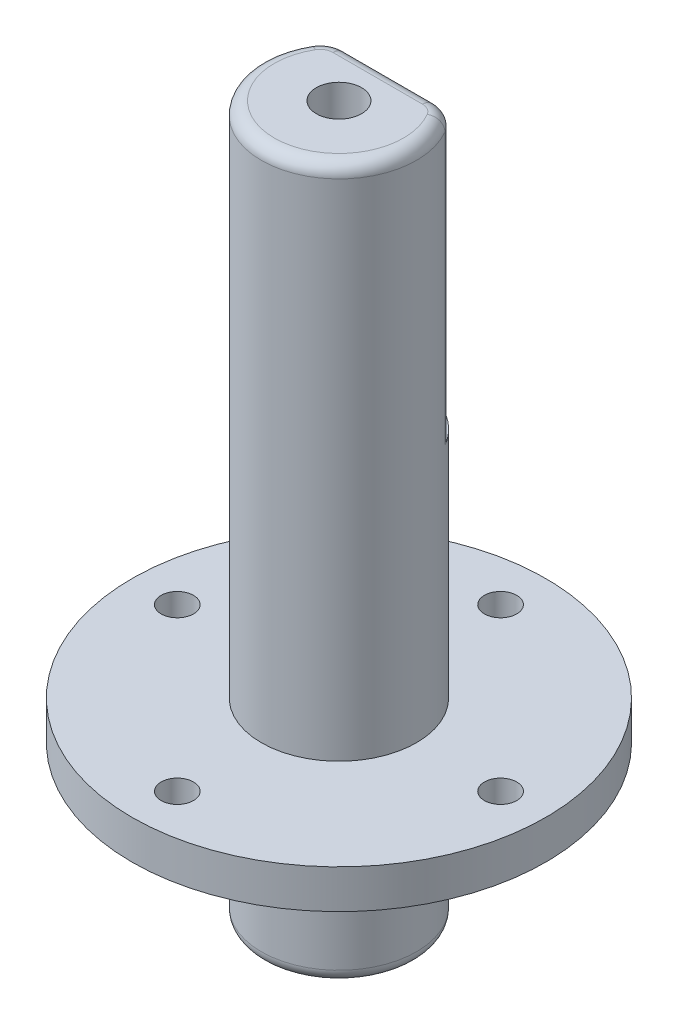
SolidWorks part; units mm, degrees
ref_plane "Front Plane" through (0, 0, 0) normal (0, 0, 1) x (1, 0, 0)
ref_plane "Top Plane" through (0, 0, 0) normal (0, 1, 0) x (1, 0, 0)
ref_plane "Right Plane" through (0, 0, 0) normal (1, 0, 0) x (0, 0, -1)
sketch "Sketch1" plane through (0, 0, 0) normal (0, 1, 0) x (1, 0, 0)
  circle A0 centre (0, 0) radius 6
  dimension "D1" = 12
extrude "Boss-Extrude1" add sketch "Sketch1" along normal blind 10
sketch "Sketch2" plane through (0, 10, 0) normal (0, 1, 0) x (1, 0, 0)
  circle A0 centre (0, 0) radius 10
  dimension "D1" = 20
extrude "Boss-Extrude2" add sketch "Sketch2" along normal blind 2
sketch "Sketch5" plane through (0, 12, 0) normal (0, 1, 0) x (1, 0, 0)
  circle A0 centre (0, 0) radius 16
  dimension "D1" = 32
extrude "Boss-Extrude3" add sketch "Sketch5" along normal blind 3
sketch "Sketch6" plane through (0, 15, 0) normal (0, 1, 0) x (1, 0, 0)
  circle A0 centre (0, 0) radius 6
  dimension "D1" = 12
extrude "Boss-Extrude4" add sketch "Sketch6" along normal blind 40
fillet "Fillet1" radius 1 1 edges at (0, 0, 6)
sketch "Sketch7" plane through (0, 55, 0) normal (0, 1, 0) x (1, 0, 0)
  line L0 (-4.4721, 4) -> (4.4721, 4)
  arc A0 (4.4721, 4) -> (-4.4721, 4) centre (0, 0) ccw
  dimension "D2" = 12
  dimension "D1" = 4
extrude "Cut-Extrude1" cut sketch "Sketch7" against normal blind 22
fillet "Fillet2" radius 2 2 edges at (-4.4721, 44, -4) (4.4721, 44, -4)
fillet "Fillet3" radius 1 4 edges at (-4.4641, 55, -3.7321) (0, 55, -4) (4.4641, 55, -3.7321) (0, 55, 6)
sketch "Sketch10" plane through (0, 55, 0) normal (0, 1, 0) x (1, 0, 0)
  circle A0 centre (0, 0) radius 1.75
  dimension "D1" = 3.5
extrude "Cut-Extrude2" cut sketch "Sketch10" against normal blind 20
sketch "Sketch11" plane through (0, 15, 0) normal (0, 1, 0) x (1, 0, 0)
  circle A0 centre (0, 0) radius 12.5 construction
  circle A1 centre (0, 12.5) radius 1.25
  circle A2 centre (12.5, 0) radius 1.25
  circle A3 centre (0, -12.5) radius 1.25
  circle A4 centre (-12.5, 0) radius 1.25
  dimension "D1" = 25
  dimension "D2" = 2.5
extrude "Cut-Extrude3" cut sketch "Sketch11" against normal blind 7
